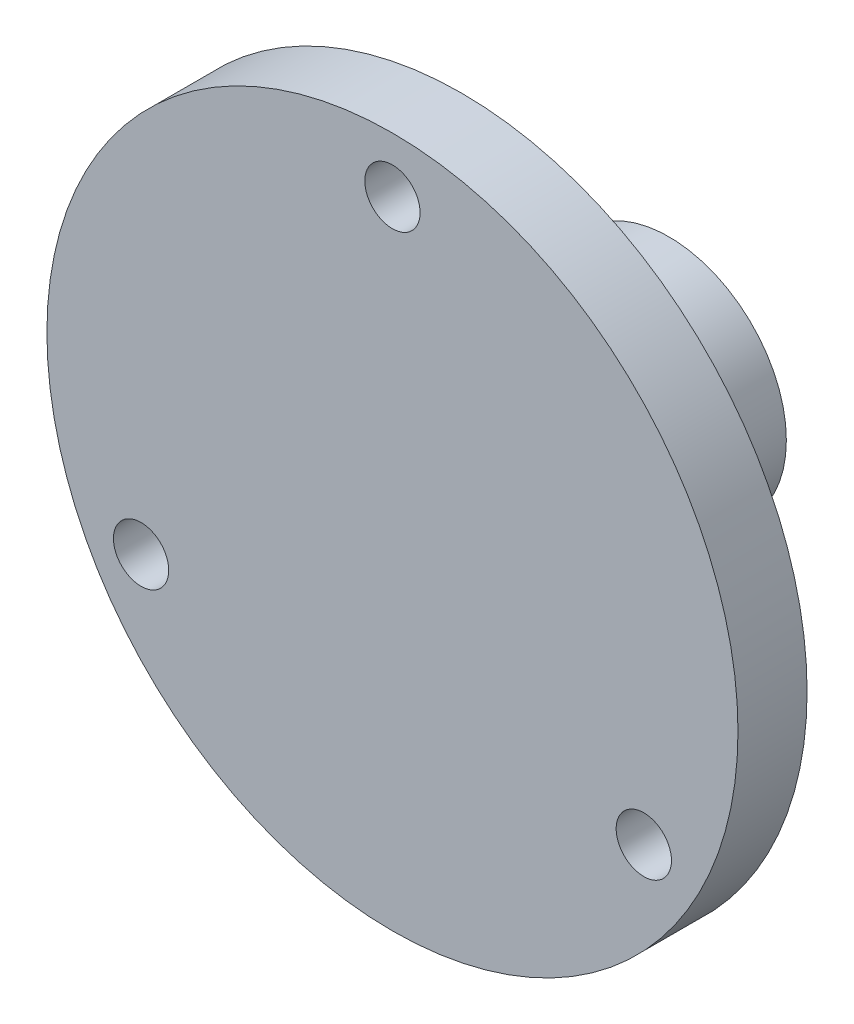
SolidWorks part; units mm, degrees
ref_plane "Plano frontal" through (0, 0, 0) normal (0, 0, 1) x (1, 0, 0)
ref_plane "Plano superior" through (0, 0, 0) normal (0, 1, 0) x (1, 0, 0)
ref_plane "Plano direito" through (0, 0, 0) normal (1, 0, 0) x (0, 0, -1)
sketch "Esboço1" plane through (0, 0, 0) normal (1, 0, 0) x (0, 0, -1)
  line L0 (0, 0) -> (200, 0) construction
  line L1 (0, 0) -> (0, 50)
  line L2 (0, 50) -> (10, 50)
  line L3 (10, 50) -> (10, 17)
  line L4 (10, 17) -> (40, 17)
  line L5 (40, 17) -> (40, 12.7)
  line L6 (40, 12.7) -> (20, 12.7)
  line L7 (20, 12.7) -> (20, 0)
  line L8 (20, 0) -> (0, 0)
  dimension "D1" = 100
  dimension "D2" = 30
  dimension "D3" = 25.4
  dimension "D4" = 10
  dimension "D5" = 10
  dimension "D6" = 34
revolve "Revolução1" add sketch "Esboço1" angle 360 about L0
sketch "Esboço2" plane through (0, 0, 0) normal (0, 0, 1) x (1, 0, 0)
  circle A0 centre (0, 42) radius 4
  circle A2 centre (36.3731, -21) radius 4
  circle A3 centre (-36.3731, -21) radius 4
  point P10 (0, 0)
  dimension "D1" = 8
  dimension "D3" = 3
  dimension "D2" = 42
extrude "Corte-extrusão4" cut sketch "Esboço2" against normal up to next
ref_plane "Plano1" through (0, 17, 0) normal (0, 1, 0) x (1, 0, 0)
hole_wizard "Furo roscado de M10x1.51" positions "Esboço3" profile "Esboço4" tap size "M10x1.5" standard "Ansi Metric"
sketch "Esboço3" plane through (0, 17, 0) normal (0, 1, 0) x (1, 0, 0)
  line L0 (17, 40) -> (-17, 40) construction
  point P0 (0, 30)
  dimension "D1" = 10
sketch "Esboço4" plane through (0, 17, -30) normal (1, 0, 0) x (0, 0, 1)
  line L0 (0, 0) -> (0, 34)
  line L1 (0, 34) -> (4.25, 34)
  line L2 (4.25, 34) -> (4.25, 0.775)
  line L3 (4.25, 0.775) -> (5.025, 0)
  line L5 (5.025, 0) -> (0, 0)
  line L6 (-4.25, 0.775) -> (-5.025, 0) construction
  line L11 (0, -6.35) -> (0, 107.95) construction
  dimension "Thru Tap Drill Dia." = 8.5
  dimension "Thru Tap Drill Depth" = 34
  dimension "Near C'Sink Dia." = 10.05
  dimension "Near C'Sink Angle" = 90
cosmetic thread "Rosca de furo1" parameters "D2"=10
pattern_circular "PadrãoCircular1" count 2 over 360 about axis through (0, 0, 0) along (0, 0, 1) of "Furo roscado de M10x1.51"
cosmetic thread "Rosca de furo2" parameters "D2"=10
